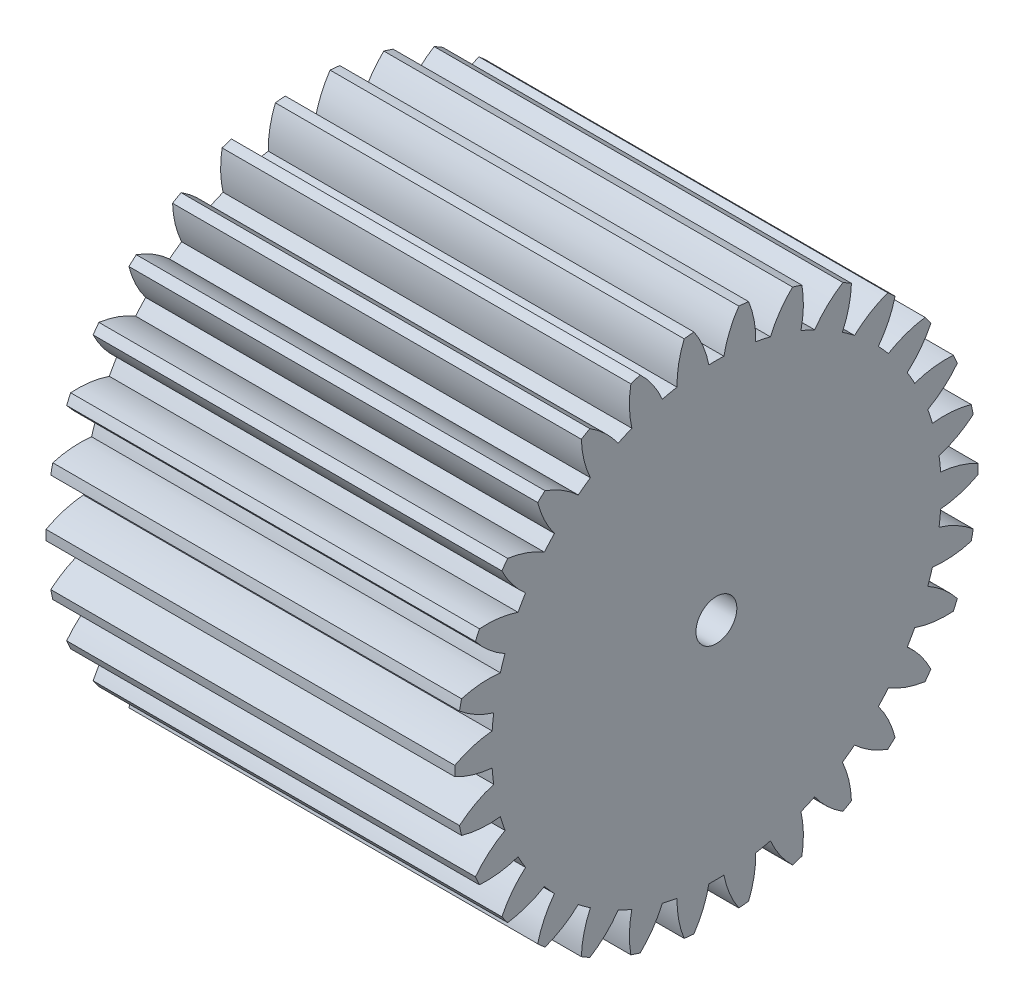
SolidWorks part; units mm, degrees
ref_plane "Plane1" through (0, 0, 0) normal (0, 0, 1) x (1, 0, 0)
ref_plane "Plane2" through (0, 0, 0) normal (0, 1, 0) x (1, 0, 0)
ref_plane "Plane3" through (0, 0, 0) normal (1, 0, 0) x (0, 0, -1)
other "Configuration Table"
sketch "HoldingSke" plane through (0, 0, 0) normal (0, 1, 0) x (1, 0, 0)
  line L0 (0, 0) -> (0.433, -0.25)
  line L1 (-15, 0) -> (100, 0) construction
  line L2 (0, 0) -> (-2.1039, 2.3779)
  line L3 (0, 0) -> (-11.863, 4.5341)
  line L4 (0, 0) -> (7.479, 4.318)
  line L5 (0, 0) -> (-46.8476, -17.4728)
  line L6 (0, 0) -> (-41.4481, -27.9652)
  line L7 (-2.1039, 2.3779) -> (8.6586, 51.2059)
  line L8 (-76.2, 54.61) -> (-75.3, 54.61)
  line L9 (-71.009, 38.7566) -> (-53.1078, 45.2721)
  line L10 (-76.2, 71.12) -> (104.1128, 71.12)
  line L11 (0, 0) -> (-50, 0)
  line L12 (-76.2, 101.6) -> (-76.133, 101.6)
  line L13 (24.9733, 27.94) -> (52.9518, 28.4284)
  line L14 (24.9733, 27.94) -> (24.9743, 27.94)
  line L15 (24.9733, 27.94) -> (100.4006, 29.5858)
  line L16 (-63.627, -2) -> (-12.827, -2)
  circle A0 centre (0, 0) radius 2.5
  circle A1 centre (0, 0) radius 27.499
  circle A2 centre (0, 0) radius 37.5
  circle A3 centre (0, 0) radius 2.5
  dimension "MHD" = 54.998
  dimension "Hub_dia" = 75
  dimension "Bore" = 5
  dimension "MBD" = 5
  dimension "Num_teeth" = 30
  dimension "Pitch" = 0.5
  dimension "Overall_len" = 50
  dimension "Show_teeth" = 30
  dimension "Thickness" = 50
  dimension "OAL" = 50.0001
  dimension "T_dim" = 0.9
  dimension "Ap" = 20
  dimension "H" = 19.05
  dimension "Pitch_radius" = 180.3128
  dimension "Width" = 50
  dimension "Backlash" = 0.067
  dimension "Addendum_fac" = 1
  dimension "Dedendum_fac" = 1.25
  dimension "Clearance_fac" = 0.25
  dimension "Dedendum_add" = 0.001
  dimension "Module" = 2
sketch "BasProSke" plane through (0, 0, 0) normal (0, 1, 0) x (1, 0, 0)
  line L0 (-10, 0) -> (60, 0) construction
  line L1 (0, 0) -> (0, 32)
  line L2 (0, 0) -> (50, 0)
  line L3 (50, 0) -> (50, 32)
  line L4 (50, 32) -> (0, 32)
  dimension "Thickness" = 50
  dimension "Diameter" = 64
revolve "Base-Revolve" add sketch "BasProSke" angle 360 about L0
sketch "TooCutSke" plane through (0, 0, 0) normal (1, 0, 0) x (0, 0, -1)
  line L1 (0, 0) -> (0, 107) construction
  line L2 (0, 0) -> (-1.6873, 29.9525) construction
  line L3 (0, 0) -> (-6.2643, 59.6013) construction
  line L4 (-1.6873, 29.9525) -> (-3.1322, 29.8007) construction
  arc A0 (0.9186, 27.4837) -> (-0.9186, 27.4837) centre (0, 0) ccw
  arc A1 (2.7618, 31.9061) -> (-2.7618, 31.9061) centre (0, 0) ccw
  circle A2 centre (0, 0) radius 30 construction
  circle A3 centre (0, 0) radius 28.1908 construction
  arc A4 (-0.9186, 27.4837) -> (-2.7618, 31.9061) centre (-12.6936, 25.1712) ccw
  arc A5 (2.7618, 31.9061) -> (0.9186, 27.4837) centre (12.6936, 25.1712) ccw
  dimension "Root_dia" = 54.998
  dimension "Overcut_dia" = 64.0508
  dimension "Pitch_dia" = 60
  dimension "Base_dia" = 56.3816
  dimension "Flank_rad" = 12
  dimension "Half_ang" = 6
  dimension "Half_CT" = 1.4528
extrude "ToothCut" cut sketch "TooCutSke" along normal through all
fillet "Breaks" [suppressed] radius 0.04
fillet "RootFillets" [suppressed] radius 0.501
pattern_circular "TeethCuts" count 30 over 360 about axis through (0, 0, 0) along (1, 0, 0) of "ToothCut", "RootFillets", "Breaks"
sketch "HubNeaOneSke" plane through (0, 0, 0) normal (-1, 0, 0) x (0, 0, 1)
  circle A0 centre (0, 0) radius 27.499
  dimension "Diameter" = 54.998
extrude "HubNearOne" [suppressed] add sketch "HubNeaOneSke" along normal blind 20.0001
sketch "HubNeaBotSke" plane through (0, 0, 0) normal (-1, 0, 0) x (0, 0, 1)
  circle A0 centre (0, 0) radius 27.499
  dimension "Diameter" = 54.998
extrude "HubNearBoth" [suppressed] add sketch "HubNeaBotSke" along normal blind 10
ref_plane "FarPln" through (50, 0, 0) normal (1, 0, 0) x (0, 0, -1)
sketch "HubFarSke" plane through (50, 0, 0) normal (1, 0, 0) x (0, 0, -1)
  circle A0 centre (0, 0) radius 27.499
  dimension "Diameter" = 54.998
extrude "HubFar" [suppressed] add sketch "HubFarSke" along normal blind 10
sketch "BorSke" plane through (0, 0, 0) normal (1, 0, 0) x (0, 0, -1)
  circle A0 centre (0, 0) radius 2.5
  dimension "Diameter" = 5
extrude "Bore" cut sketch "BorSke" along normal mid plane 100.0001
sketch "KeySke" plane through (0, 0, 0) normal (1, 0, 0) x (0, 0, -1)
  line L0 (-1, 0) -> (-1, 3.4)
  line L1 (-1, 3.4) -> (1, 3.4)
  line L2 (1, 3.4) -> (1, 0)
  line L3 (0, 0) -> (0, 34) construction
  line L4 (-1, 0) -> (1, 0)
  dimension "Offset" = 3.4
  dimension "Width" = 2
extrude "Keyway" [suppressed] cut sketch "KeySke" along normal mid plane 100.0001
pattern_circular "Keyway2" [suppressed] count 2 every 90 about axis through (-10, 0, 0) along (1, 0, 0)
equation "' \"Module@HoldingSke\" = 6.35"
equation "' \"Num_teeth@HoldingSke\" = 12"
equation "' \"Ap@HoldingSke\" =  20"
equation "' \"Ap@HoldingSke\" = 20"
equation "' \"Width@HoldingSke\" = 0.5 * 25.4"
equation "' \"Hub_dia@HoldingSke\"= 1 * 25.4"
equation "' \"Hub_dia@HoldingSke\" = 1 * 25.4"
equation "' \"Overall_len@HoldingSke\" = 1.0 * 25.4"
equation "' \"Bore@HoldingSke\" = 0.75 * 25.4"
equation "' \"T_dim@HoldingSke\" = 0.1 * 25.4"
equation "' \"Width@KeySke\" = 0.25 * 25.4"
equation "' \"Show_teeth@HoldingSke\" = 13"
equation "' \"Backlash@HoldingSke\" = 0.009 * 25.4"
equation "' \"Addendum_fac@HoldingSke\" = 1.0"
equation "' \"Dedendum_fac@HoldingSke\" = 1.25"
equation "' \"Dedendum_add@HoldingSke\" = 0.00005 * 25.4"
equation "' \"Clearance_fac@HoldingSke\" = 0.25"
equation "\"Pitch@HoldingSke\" = 1 / \"Module@HoldingSke\""
equation "\"Overcut_dia@TooCutSke\" = (\"Num_teeth@HoldingSke\" + 2 * \"Addendum_fac@HoldingSke\") / \"Pitch@HoldingSke\" + 0.002 * 25.4"
equation "\"Pitch_dia@TooCutSke\" = \"Num_teeth@HoldingSke\" / \"Pitch@HoldingSke\""
equation "\"Base_dia@TooCutSke\" = \"Num_teeth@HoldingSke\" / \"Pitch@HoldingSke\" * cos((\"Ap@HoldingSke\"  * 3.14159265 / 180))"
equation "\"Root_dia@TooCutSke\" = (\"Num_teeth@HoldingSke\" + 2) / \"Pitch@HoldingSke\" - 2 * (\"Addendum_fac@HoldingSke\" + \"Dedendum_fac@HoldingSke\") / \"Pitch@HoldingSke\" - \"Dedendum_add@HoldingSke\" * 2"
equation "\"Half_ang@TooCutSke\" = 180 / \"Num_teeth@HoldingSke\""
equation "\"Half_CT@TooCutSke\" = \"Num_teeth@HoldingSke\" / \"Pitch@HoldingSke\" * sin((3.14159265 / 2 / \"Num_teeth@HoldingSke\")) / 2 - 7 * \"Backlash@HoldingSke\" / 4"
equation "\"Flank_rad@TooCutSke\" = \"Num_teeth@HoldingSke\" / \"Pitch@HoldingSke\" / 5"
equation "\"Radius@RootFillets\" = \"Clearance_fac@HoldingSke\" / \"Pitch@HoldingSke\" + \"Dedendum_add@HoldingSke\""
equation "\"Break_rad@Breaks\" = 0.02 / \"Pitch@HoldingSke\""
equation "\"Thickness@HoldingSke\" = \"Width@HoldingSke\""
equation "\"OAL@HoldingSke\" = \"Thickness@HoldingSke\""
equation "\"MHD@HoldingSke\" = (\"Num_teeth@HoldingSke\" + 2) / \"Pitch@HoldingSke\" - 2 * (\"Addendum_fac@HoldingSke\" + \"Dedendum_fac@HoldingSke\")  / \"Pitch@HoldingSke\" - \"Dedendum_add@HoldingSke\" * 2"
equation "\"MBD@HoldingSke\" = (\"Num_teeth@HoldingSke\" + 2) / \"Pitch@HoldingSke\" - 2 * (\"Addendum_fac@HoldingSke\" + \"Dedendum_fac@HoldingSke\")  / \"Pitch@HoldingSke\" - \"Dedendum_add@HoldingSke\" * 2 - 0.002 * 25.4"
equation "\"MHD@HoldingSke\" = ((sgn( \"MHD@HoldingSke\" - \"Hub_dia@HoldingSke\" )-1)*( \"MHD@HoldingSke\" - \"Hub_dia@HoldingSke\" ))/-2+ \"Hub_dia@HoldingSke\""
equation "\"MBD@HoldingSke\" = ((sgn( \"MBD@HoldingSke\" - \"Bore@HoldingSke\" )-1)*( \"MBD@HoldingSke\" - \"Bore@HoldingSke\" ))/-2+ \"Bore@HoldingSke\""
equation "\"OAL@HoldingSke\" = ((sgn( \"OAL@HoldingSke\" - \"Overall_len@HoldingSke\" )+1)*( \"OAL@HoldingSke\" - \"Overall_len@HoldingSke\" ))/2 + \"Overall_len@HoldingSke\" + 0.000002 * 25.4"
equation "\"Num_teeth@TeethCuts\" = int( \"Show_teeth@HoldingSke\" ) + 1"
equation "\"Num_teeth@TeethCuts\" = ((sgn( \"Num_teeth@TeethCuts\" - \"Num_teeth@HoldingSke\" )-1)*( \"Num_teeth@TeethCuts\" - \"Num_teeth@HoldingSke\" ))/-2+ \"Num_teeth@HoldingSke\""
equation "\"Num_teeth@TeethCuts\" = ((sgn( \"Num_teeth@TeethCuts\" - 2.0)+1)*( \"Num_teeth@TeethCuts\" - 2.0))/2 +2.0"
equation "\"Angle@TeethCuts\" = 360.0 / \"Num_teeth@HoldingSke\""
equation "\"Diameter@BasProSke\" = (\"Num_teeth@HoldingSke\" + 2 * \"Addendum_fac@HoldingSke\") / \"Pitch@HoldingSke\""
equation "\"Thickness@BasProSke\"  = \"Thickness@HoldingSke\""
equation "' \"Fillet_rad@BasProSke\" =  \"Thickness@HoldingSke\" * 0.05"
equation "' \"Fillet_rad@BasProSke\" = \"Thickness@HoldingSke\" * 0.05"
equation "\"MHD@HoldingSke\" = ((sgn( \"MHD@HoldingSke\" - \"Root_dia@TooCutSke\" )-1)*( \"MHD@HoldingSke\" - \"Root_dia@TooCutSke\" ))/-2+ \"Root_dia@TooCutSke\""
equation "\"Diameter@HubNeaOneSke\" = \"MHD@HoldingSke\""
equation "\"Length@HubNearOne\" = \"OAL@HoldingSke\" - \"Thickness@BasProSke\""
equation "\"Diameter@HubNeaBotSke\" = \"MHD@HoldingSke\""
equation "\"Length@HubNearBoth\" = ( \"OAL@HoldingSke\" - \"Thickness@BasProSke\" ) / 2.0"
equation "\"Thickness@FarPln\" = \"Thickness@BasProSke\""
equation "\"Diameter@HubFarSke\" = \"MHD@HoldingSke\""
equation "\"Length@HubFar\" = ( \"OAL@HoldingSke\" - \"Thickness@BasProSke\" ) / 2.0"
equation "\"Diameter@BorSke\" = \"MBD@HoldingSke\""
equation "\"D1@Bore\" = \"OAL@HoldingSke\" * 2.0"
equation "\"D1@Keyway\" = \"OAL@HoldingSke\" * 2.0"
equation "\"Offset@KeySke\" = \"T_dim@HoldingSke\" + \"MBD@HoldingSke\" / 2.0"
